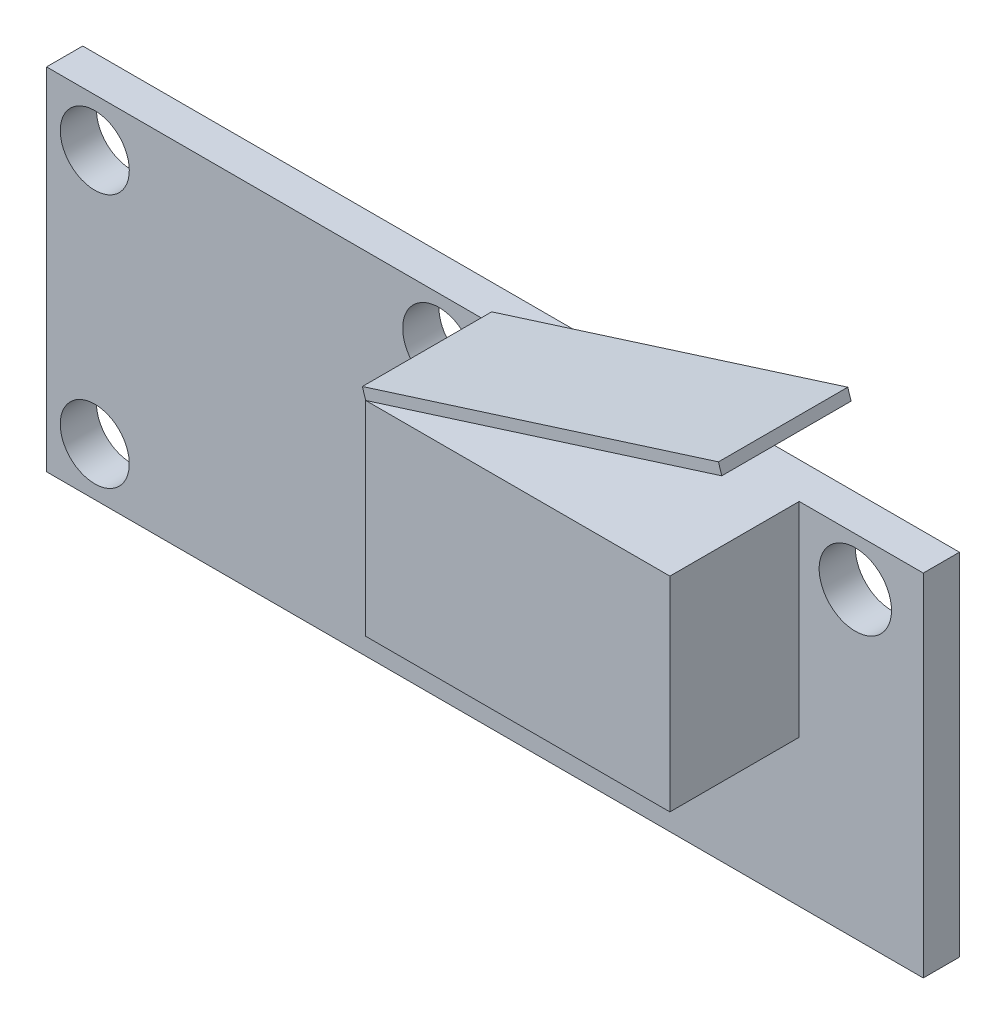
SolidWorks part; units mm, degrees
ref_plane "Piano frontale" through (0, 0, 0) normal (0, 0, 1) x (1, 0, 0)
ref_plane "Piano superiore" through (0, 0, 0) normal (0, 1, 0) x (1, 0, 0)
ref_plane "Piano destro" through (0, 0, 0) normal (1, 0, 0) x (0, 0, -1)
sketch "Schizzo1" plane through (0, 0, 0) normal (0, 0, 1) x (1, 0, 0)
  line L0 (40, 13.8) -> (0, 13.8) construction
  line L1 (0, 0) -> (40, 0)
  line L2 (0, 0) -> (0, 16)
  line L3 (0, 16) -> (40, 16)
  line L4 (40, 0) -> (40, 16)
  line L5 (2.2, 18.0305) -> (2.2, -3.4999) construction
  line L6 (0, 8) -> (40, 8) construction
  circle A0 centre (36.9, 13.8) radius 1.65
  circle A1 centre (17.9, 13.8) radius 1.65
  circle A2 centre (2.2, 13.8) radius 1.575
  circle A3 centre (2.2, 2.2) radius 1.575
  dimension "D4" = 3.1
  dimension "D5" = 3.3
  dimension "D1" = 40
  dimension "D2" = 16
  dimension "D3" = 19
  dimension "D6" = 2.2
  dimension "D7" = 2.2
extrude "Estrusione-Estrusione1" add sketch "Schizzo1" along normal blind 1.65
sketch "Schizzo2" plane through (0, 0, 1.65) normal (0, 0, 1) x (1, 0, 0)
  line L0 (27.4, 18.424) -> (27.4, -4.1046) construction
  line L1 (40, 16) -> (0, 16) construction
  line L2 (34.3398, 6.6825) -> (20.4602, 6.6825)
  line L3 (34.3398, 6.6825) -> (34.3398, 16)
  line L4 (34.3398, 16) -> (20.4602, 16)
  line L5 (20.4602, 6.6825) -> (20.4602, 16)
  line L6 (34.3398, 6.6825) -> (20.4602, 16) construction
  line L7 (34.3398, 16) -> (20.4602, 6.6825) construction
  circle A0 centre (36.9, 13.8) radius 1.65 construction
  circle A1 centre (17.9, 13.8) radius 1.65 construction
  point P6 (27.4, 11.3413)
extrude "Estrusione-Estrusione2" add sketch "Schizzo2" along normal blind 5.9
sketch "Schizzo3" plane through (0, 0, 1.65) normal (0, 0, 1) x (1, 0, 0)
  line L0 (20.4602, 16) -> (36.7064, 21.145)
extrude "Estrusione-Sottile1" add sketch "Schizzo3" along normal blind 5.9 separate body thin thin type one direction reverse wall 0.5
